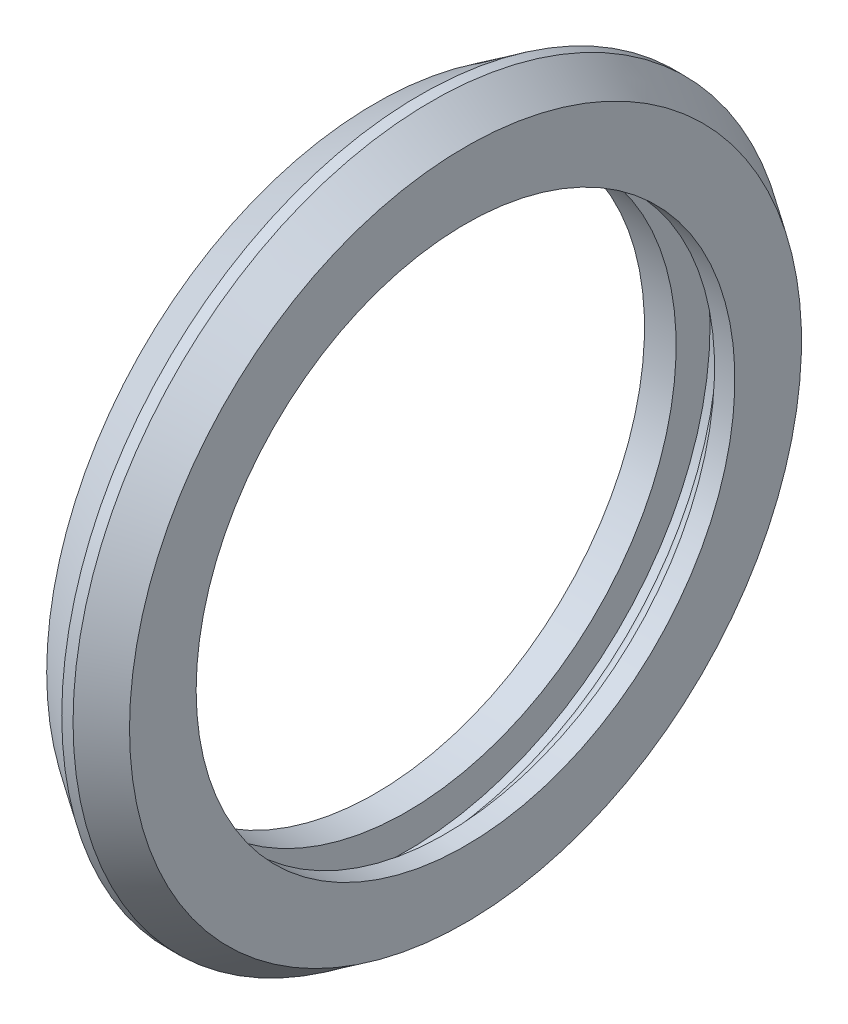
SolidWorks part; units mm, degrees
ref_plane "Спереди" through (0, 0, 0) normal (0, 0, 1) x (1, 0, 0)
ref_plane "Сверху" through (0, 0, 0) normal (0, 1, 0) x (1, 0, 0)
ref_plane "Справа" through (0, 0, 0) normal (1, 0, 0) x (0, 0, -1)
other "Configuration Table"
sketch "Эскиз1" plane through (0, 0, 0) normal (0, 1, 0) x (1, 0, 0)
  line L0 (0, 0) -> (19.5415, 0)
  line L1 (0, 0) -> (0, 26.85)
  line L2 (-3.5, 26.85) -> (3.5, 26.85)
  line L3 (-3.5, 29.75) -> (-0.5, 31.75)
  line L4 (-3.5, 26.85) -> (3.5, 26.85)
  line L5 (-3.5, 26.85) -> (-3.5, 29.75)
  line L6 (-0.5, 31.75) -> (0.5, 31.75)
  line L7 (3.5, 26.85) -> (3.5, 29.75)
  line L8 (0.5, 31.75) -> (3.5, 29.75)
  line L9 (-3.5, 29.75) -> (-4.5, 29.0833)
  line L10 (-3.5, 26.85) -> (-1.7, 26.85)
  line L11 (-3.5, 26.85) -> (-3.5, 23.85)
  line L12 (-3.5, 23.85) -> (-1.7, 23.85)
  line L13 (-1.7, 26.85) -> (-1.7, 23.85)
  line L14 (3.5, 26.85) -> (1.7, 26.85)
  line L15 (3.5, 26.85) -> (3.5, 23.85)
  line L16 (3.5, 23.85) -> (1.7, 23.85)
  line L17 (1.7, 26.85) -> (1.7, 23.85)
  line L18 (-4.5, 29.0833) -> (-4.5, 23.85)
  line L19 (-4.5, 23.85) -> (-3.5, 23.85)
  circle A0 centre (0, 26.85) radius 0.75
  point P4 (3.5, 31.75)
  point P7 (0, 26.85)
  point P8 (-3.5, 31.75)
  dimension "D4" = 1.5
  dimension "D1" = 26.85
  dimension "D2" = 7
  dimension "D3" = 4.9
  dimension "D10" = 2
  dimension "D5" = 3
  dimension "D8" = 3
  dimension "D9" = 3.4
  dimension "D11" = 2
  dimension "D12" = 1
revolve "Повернуть1" add sketch "Эскиз1" angle 360 about L0
